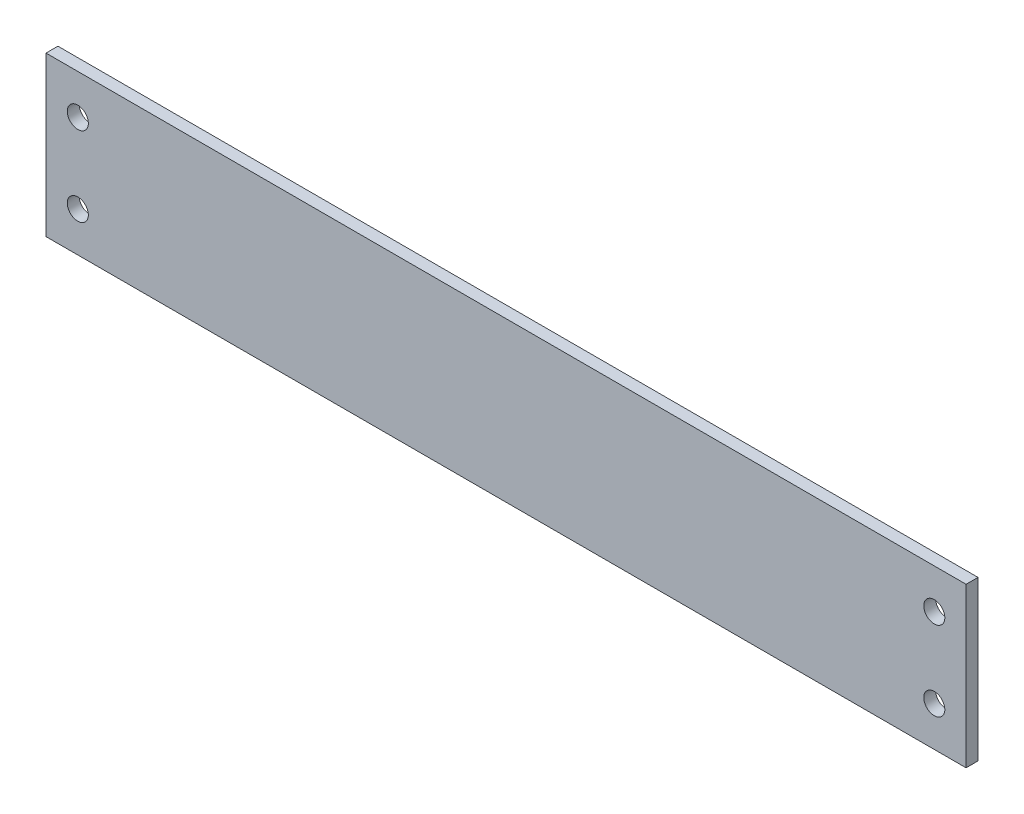
SolidWorks part; units mm, degrees
ref_plane "Front Plane" through (0, 0, 0) normal (0, 0, 1) x (1, 0, 0)
ref_plane "Top Plane" through (0, 0, 0) normal (0, 1, 0) x (1, 0, 0)
ref_plane "Right Plane" through (0, 0, 0) normal (1, 0, 0) x (0, 0, -1)
sketch "Extrusion Base Sketch" plane through (0, 0, 0) normal (0, 0, 1) x (1, 0, 0)
  line L0 (209.5, 36.75) -> (209.5, -3.25)
  line L1 (0, 0) -> (187.5, 0) construction
  line L2 (0, 0) -> (0, 33.5) construction
  line L3 (0, 33.5) -> (187.5, 33.5) construction
  line L4 (187.5, 0) -> (187.5, 33.5) construction
  line L5 (-22, 36.75) -> (209.5, 36.75)
  line L6 (-3.25, 36.75) -> (-3.25, -3.25) construction
  line L7 (-22, -3.25) -> (209.5, -3.25)
  line L8 (190.75, 36.75) -> (190.75, -3.25) construction
  line L9 (-22, 36.75) -> (-22, -3.25)
  line L10 (201.5, 26.75) -> (201.5, 6.75) construction
  line L11 (201.5, 16.75) -> (209.5, 16.75) construction
  circle A0 centre (-14, 26.75) radius 2.65
  circle A1 centre (-14, 6.75) radius 2.65
  circle A2 centre (201.5, 26.75) radius 2.65
  circle A3 centre (201.5, 6.75) radius 2.65
  point P20 (0, 0)
  point P23 (0, 0)
  point P26 (0, 0)
  point P27 (0, 0)
  point P28 (0, 0)
  point P29 (201.5, 27.5378)
  point P30 (201.5, 23.9101)
  point P31 (0, 0)
  point P32 (-3.25, -9.6658)
  point P33 (-43.4486, 31.5685)
  point P34 (190.75, -11.3808)
  point P35 (190.75, 41.4243)
  point P36 (0, 0)
  point P37 (0, 0)
  dimension "D8" = 5.3
  dimension "D1" = 33.5
  dimension "D2" = 187.5
  dimension "D4" = 3.25
  dimension "D5" = 3.25
  dimension "D6" = 3.25
  dimension "D7" = 20
  dimension "D3" = 40
extrude "Extrusion Base Extrude" add sketch "Extrusion Base Sketch" against normal blind 3
equation "\"Logo Height\"= 33.5mm"
equation "\"Total Height\" = 40mm"
equation "\"Border\"= ( \"Total Height\" - \"Logo Height\" ) / 2"
equation "\"Logo Length\"= 187.5mm"
equation "\"D1@Extrusion Base Sketch\" = \"Logo Height\""
equation "\"D2@Extrusion Base Sketch\" = \"Logo Length\""
equation "\"D4@Extrusion Base Sketch\" = \"Border\""
equation "\"D5@Extrusion Base Sketch\" = \"Border\""
equation "\"D6@Extrusion Base Sketch\" = \"Border\""
equation "\"D3@Extrusion Base Sketch\" = \"Total Height\""
